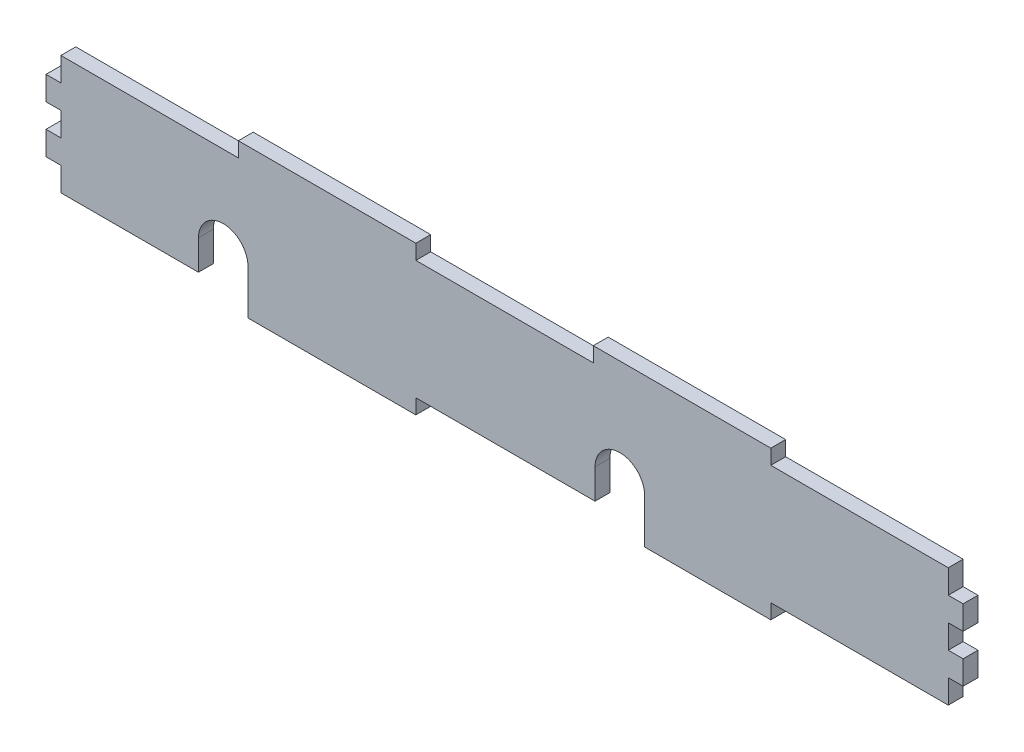
SolidWorks part; units mm, degrees
ref_plane "Front Plane" through (0, 0, 0) normal (0, 0, 1) x (1, 0, 0)
ref_plane "Top Plane" through (0, 0, 0) normal (0, 1, 0) x (1, 0, 0)
ref_plane "Right Plane" through (0, 0, 0) normal (1, 0, 0) x (0, 0, -1)
sketch "Sketch1" plane through (0, 0, 0) normal (0, 0, 1) x (1, 0, 0)
  line L6 (-4.9554, 4.8) -> (-7.9554, 4.8)
  line L16 (177.0446, 4.8) -> (174.0446, 4.8)
  line L55 (22.7946, 6) -> (22.7946, 0)
  line L56 (32.7946, 6) -> (32.7946, -3)
  line L59 (112.7946, 6) -> (112.7946, 0)
  line L62 (30.8446, 27) -> (66.6446, 27)
  line L65 (-7.9554, 19.2) -> (-7.9554, 14.4)
  line L66 (-4.9554, 0) -> (-4.9554, 4.8)
  line L67 (-4.9554, 14.4) -> (-7.9554, 14.4)
  line L68 (-4.9554, 24) -> (30.8446, 24)
  line L69 (30.8446, 24) -> (30.8446, 27)
  line L70 (-4.9554, 9.6) -> (-4.9554, 14.4)
  line L71 (-7.9554, 9.6) -> (-4.9554, 9.6)
  line L72 (-7.9554, 9.6) -> (-7.9554, 4.8)
  line L73 (-4.9554, 19.2) -> (-4.9554, 24)
  line L74 (-7.9554, 19.2) -> (-4.9554, 19.2)
  line L75 (-4.9554, 24) -> (-7.9554, 24) [skipped]
  line L76 (177.0446, 19.2) -> (177.0446, 14.4)
  line L77 (174.0446, 4.8) -> (174.0446, 0)
  line L79 (66.6446, 24) -> (66.6446, 27)
  line L80 (102.4446, 24) -> (102.4446, 27)
  line L81 (177.0446, 14.4) -> (174.0446, 14.4)
  line L82 (174.0446, 14.4) -> (174.0446, 9.6)
  line L83 (174.0446, 9.6) -> (177.0446, 9.6)
  line L84 (177.0446, 9.6) -> (177.0446, 4.8)
  line L85 (174.0446, 24) -> (174.0446, 19.2)
  line L86 (174.0446, 19.2) -> (177.0446, 19.2)
  line L87 (177.0446, 24) -> (174.0446, 24) [skipped]
  line L88 (66.6446, 24) -> (102.4446, 24)
  line L89 (138.2446, 24) -> (138.2446, 27)
  line L96 (-4.9554, 0) -> (22.7946, 0)
  line L97 (138.2446, 24) -> (174.0446, 24)
  line L98 (102.4446, 27) -> (138.2446, 27)
  line L101 (317.2446, 24) -> (317.2446, 27) [skipped]
  line L102 (245.6446, 24) -> (245.6446, 27) [skipped]
  line L103 (209.8446, 24) -> (245.6446, 24) [skipped]
  line L104 (174.0446, 24) -> (174.0446, 27) [skipped]
  line L105 (138.2446, 24) -> (174.0446, 24) [skipped]
  line L107 (32.7946, -3) -> (66.6446, -3)
  line L108 (66.6446, -3) -> (66.6446, 0)
  line L111 (138.2446, -3) -> (138.2446, 0)
  line L112 (66.6446, 0) -> (102.4446, 0)
  line L113 (138.2446, 0) -> (174.0446, 0)
  line L114 (102.7946, 6) -> (102.7946, 0)
  line L115 (112.7946, 0) -> (112.7946, -3)
  line L116 (112.7946, -3) -> (138.2446, -3)
  line L117 (102.4446, 0) -> (102.7946, 0)
  line L119 (102.4446, -3) -> (102.7946, -3) [skipped]
  arc A0 (32.7946, 6) -> (22.7946, 6) centre (27.7946, 6) ccw
  arc A2 (112.7946, 6) -> (102.7946, 6) centre (107.7946, 6) ccw
  dimension "D2" = 4.8
  dimension "D13" = 10
  dimension "D14" = 10
  dimension "D3" = 5
  dimension "D4" = 3
  dimension "D5" = 4.8
  dimension "D7" = 3
  dimension "D8" = 35.8
  dimension "D15" = 3
  dimension "D16" = 179
  dimension "D18" = 2
  dimension "D6" = 3
  dimension "D10" = 35.8
extrude "Boss-Extrude1" add sketch "Sketch1" along normal blind 3
